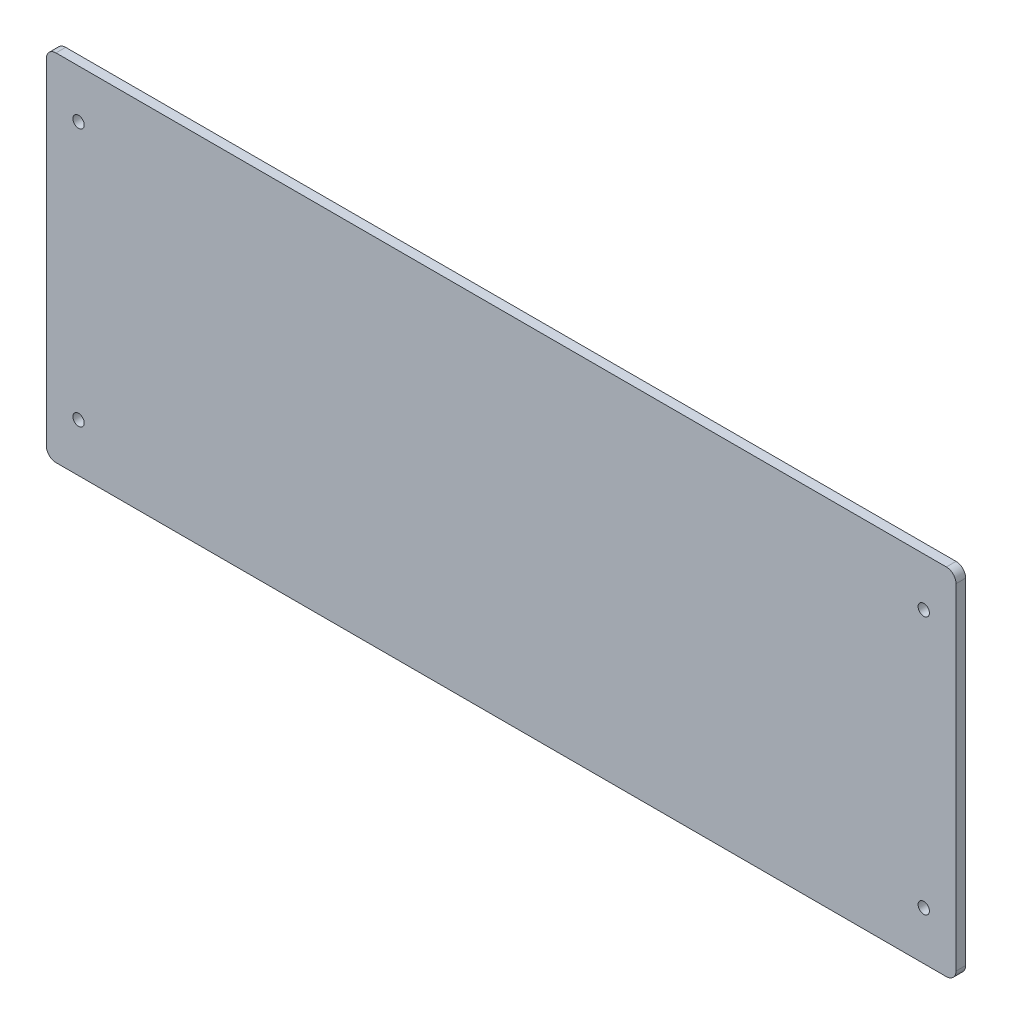
SolidWorks part; units mm, degrees
ref_plane "Front Plane" through (0, 0, 0) normal (0, 0, 1) x (1, 0, 0)
ref_plane "Top Plane" through (0, 0, 0) normal (0, 1, 0) x (1, 0, 0)
ref_plane "Right Plane" through (0, 0, 0) normal (1, 0, 0) x (0, 0, -1)
sketch "Sketch1" plane through (0, 0, 0) normal (0, 0, 1) x (1, 0, 0)
  line L0 (34.8, 267.5) -> (60.7, 267.5) construction
  line L1 (-138, 334) -> (138, 334)
  line L2 (-141, 331) -> (-141, 227)
  line L3 (-138, 224) -> (138, 224)
  line L4 (141, 331) -> (141, 227)
  line L5 (-131, 324.9737) -> (-131, 324.1945) construction
  line L6 (131, 323.0208) -> (131, 323.9696) construction
  line L7 (34.8, 299) -> (60.7, 299) construction
  line L8 (34.5, 298.7) -> (34.5, 275.8) construction
  line L9 (34.8, 275.5) -> (60.7, 275.5) construction
  line L10 (61, 298.7) -> (61, 275.8) construction
  line L11 (34.5, 299) -> (61, 275.5) construction
  line L12 (34.5, 275.5) -> (61, 299) construction
  line L13 (34.5, 267.2) -> (34.5, 244.3) construction
  line L14 (34.8, 244) -> (60.7, 244) construction
  line L15 (61, 267.2) -> (61, 244.3) construction
  line L16 (34.5, 267.5) -> (61, 244) construction
  line L17 (34.5, 244) -> (61, 267.5) construction
  arc A0 (-141, 227) -> (-138, 224) centre (-138, 227) ccw
  arc A1 (-138, 334) -> (-141, 331) centre (-138, 331) ccw
  arc A2 (138, 224) -> (141, 227) centre (138, 227) ccw
  arc A3 (138, 334) -> (141, 331) centre (138, 331) cw
  circle A4 centre (-131, 319) radius 1.75
  circle A5 centre (-131, 239) radius 1.75
  circle A6 centre (131, 239) radius 1.75
  circle A7 centre (131, 319) radius 1.75
  arc A8 (34.5, 275.8) -> (34.8, 275.5) centre (34.8, 275.8) ccw construction
  arc A9 (60.7, 275.5) -> (61, 275.8) centre (60.7, 275.8) ccw construction
  arc A10 (60.7, 299) -> (61, 298.7) centre (60.7, 298.7) cw construction
  arc A11 (34.8, 299) -> (34.5, 298.7) centre (34.8, 298.7) ccw construction
  arc A12 (34.5, 244.3) -> (34.8, 244) centre (34.8, 244.3) ccw construction
  arc A13 (60.7, 244) -> (61, 244.3) centre (60.7, 244.3) ccw construction
  arc A14 (60.7, 267.5) -> (61, 267.2) centre (60.7, 267.2) cw construction
  arc A15 (34.8, 267.5) -> (34.5, 267.2) centre (34.8, 267.2) ccw construction
  circle A16 centre (-54.1982, 285.255) radius 10 construction
  point P8 (-141, 334)
  point P11 (141, 224)
  point P14 (141, 334)
  point P21 (47.75, 287.25)
  point P45 (47.75, 255.75)
  dimension "D3" = 3
  dimension "D4" = 3.5
  dimension "D5" = 3.5
  dimension "D6" = 15
  dimension "D7" = 15
  dimension "D8" = 3.5
  dimension "D9" = 15
  dimension "D10" = 3.5
  dimension "D11" = 15
  dimension "D14" = 0.3
  dimension "D17" = 0.3
  dimension "D20" = 20
  dimension "D1" = 282
  dimension "D2" = 110
  dimension "D12" = 23.5
  dimension "D13" = 26.5
  dimension "D15" = 23.5
  dimension "D16" = 26.5
  dimension "D18" = 8
  dimension "D19" = 20
  dimension "D21" = 80
extrude "Boss-Extrude1" add sketch "Sketch1" along normal blind 3
